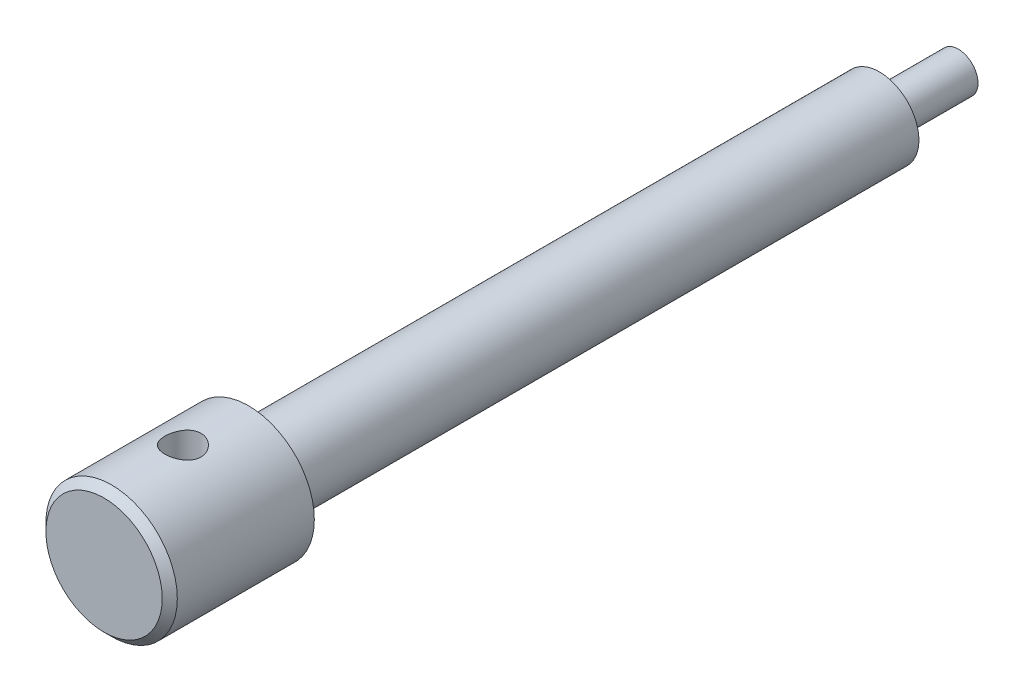
SolidWorks part; units mm, degrees
material "Plain Carbon Steel"
ref_plane "Front Plane" through (0, 0, 0) normal (0, 0, 1) x (1, 0, 0)
ref_plane "Top Plane" through (0, 0, 0) normal (0, 1, 0) x (1, 0, 0)
ref_plane "Right Plane" through (0, 0, 0) normal (1, 0, 0) x (0, 0, -1)
sketch "Sketch3" plane through (0, 0, 0) normal (0, 0, 1) x (1, 0, 0)
  circle A0 centre (0, 0) radius 10
  dimension "D1" = 20
extrude "Boss-Extrude1" add sketch "Sketch3" against normal blind 22
sketch "Sketch4" plane through (0, 0, -22) normal (0, 0, -1) x (-1, 0, 0)
  circle A0 centre (0, 0) radius 6
  dimension "D1" = 12
extrude "Boss-Extrude2" add sketch "Sketch4" along normal blind 96
cosmetic thread "Cosmetic Thread1" parameters "D1"=90, "D2"=10.072
sketch "Sketch5" plane through (0, 0, -118) normal (0, 0, -1) x (-1, 0, 0)
  circle A0 centre (0, 0) radius 3
  dimension "D1" = 6
extrude "Boss-Extrude3" add sketch "Sketch5" along normal blind 12
sketch "Sketch6" plane through (0, 0, 0) normal (0, 1, 0) x (1, 0, 0)
  circle A0 centre (0, 12) radius 2.75
  point P2 (0, 0)
  dimension "D1" = 5.5
  dimension "D2" = 12
extrude "Cut-Extrude2" cut sketch "Sketch6" against normal through all both and the other way through all
chamfer "Chamfer1" distance 1.15 angle 45 1 edges at (10, 0, 0)
